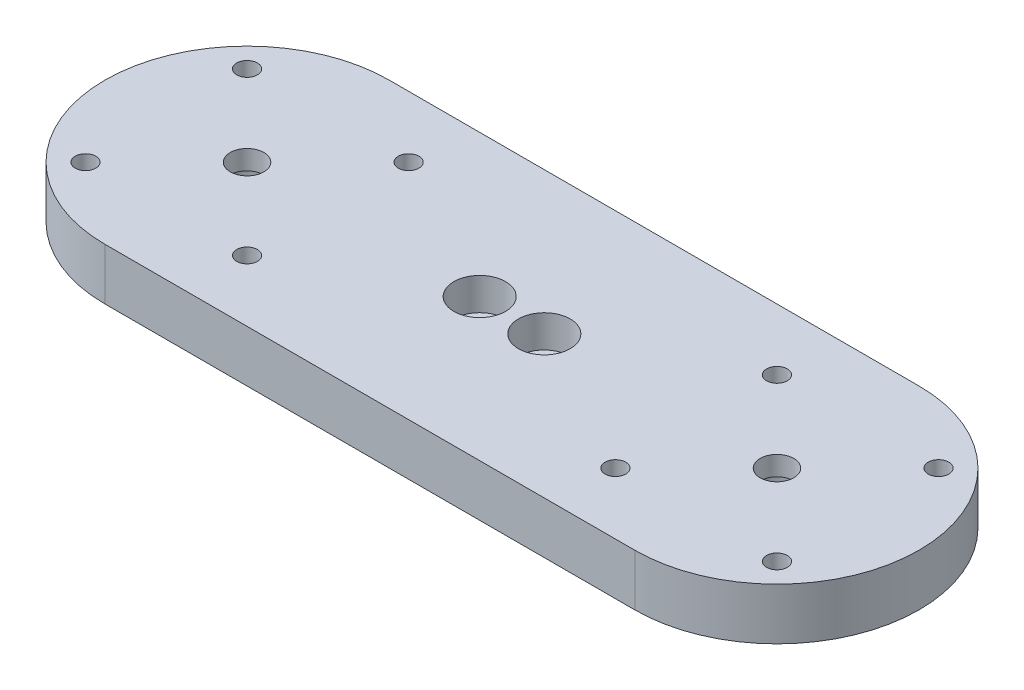
SolidWorks part; units mm, degrees
ref_plane "前视基准面" through (0, 0, 0) normal (0, 0, 1) x (1, 0, 0)
ref_plane "上视基准面" through (0, 0, 0) normal (0, 1, 0) x (1, 0, 0)
ref_plane "右视基准面" through (0, 0, 0) normal (1, 0, 0) x (0, 0, -1)
other "Configuration Table"
sketch "草图1" plane through (0, 0, 0) normal (0, 1, 0) x (1, 0, 0)
  line L0 (0, 22.5) -> (0, -22.5) construction
  line L1 (-22.5, 0) -> (22.5, 0) construction
  line L2 (0, 0) -> (15.9099, 15.9099) construction
  line L3 (0, 0) -> (82, 0) construction
  line L8 (0, 22) -> (82, 22)
  line L9 (0, -22) -> (82, -22)
  line L10 (41, 22) -> (41, -22) construction
  circle A5 centre (0, 0) radius 2.6
  arc A16 (0, 22) -> (0, -22) centre (0, 0) ccw
  arc A17 (82, -22) -> (82, 22) centre (82, 0) ccw
  circle A21 centre (82, 0) radius 2.6
  circle A22 centre (12.5, 12.5) radius 1.6
  circle A23 centre (-12.5, 12.5) radius 1.6
  circle A24 centre (12.5, -12.5) radius 1.6
  circle A25 centre (-12.5, -12.5) radius 1.6
  circle A26 centre (94.5, -12.5) radius 1.6
  circle A27 centre (69.5, -12.5) radius 1.6
  circle A28 centre (69.5, 12.5) radius 1.6
  circle A29 centre (94.5, 12.5) radius 1.6
  circle A30 centre (36, 0) radius 1.6
  circle A31 centre (46, 0) radius 1.6
  point P17 (41, 0)
  point P36 (0, 0)
  dimension "D1" = 82
  dimension "D2" = 3.2
  dimension "D5" = 5.2
  dimension "D7" = 3.2
  dimension "D6" = 22
  dimension "D3" = 45
  dimension "D4" = 25
  dimension "D8" = 10
extrude "凸台-拉伸1" add sketch "草图1" along normal blind 8
sketch "草图2" plane through (0, 0, 0) normal (0, -1, 0) x (-1, 0, 0)
  circle A0 centre (0, 0) radius 4.5
  circle A1 centre (-82, 0) radius 4.5
  dimension "D1" = 9
  dimension "D2" = 9
extrude "切除-拉伸1" cut sketch "草图2" against normal blind 5
sketch "草图3" plane through (0, 8, 0) normal (0, 1, 0) x (1, 0, 0)
  circle A0 centre (36, 0) radius 4
  circle A1 centre (46, 0) radius 4
  dimension "D1" = 8
  dimension "D2" = 8
extrude "切除-拉伸2" cut sketch "草图3" against normal blind 5
